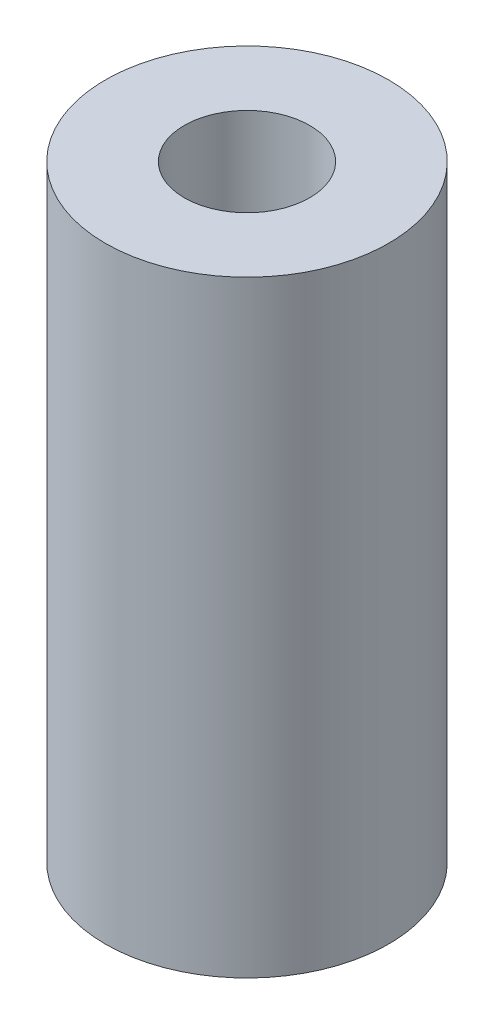
SolidWorks part; units mm, degrees
ref_plane "前视基准面" through (0, 0, 0) normal (0, 0, 1) x (1, 0, 0)
ref_plane "上视基准面" through (0, 0, 0) normal (0, 1, 0) x (1, 0, 0)
ref_plane "右视基准面" through (0, 0, 0) normal (1, 0, 0) x (0, 0, -1)
other "Configuration Table"
sketch "Sketch1" plane through (0, 0, 0) normal (0, 1, 0) x (1, 0, 0)
  circle A0 centre (0, 0) radius 3.5
  circle A1 centre (0, 0) radius 1.55
  dimension "D1" = 7
  dimension "D2" = 3.1
extrude "Boss-Extrude1" add sketch "Sketch1" along normal blind 15
